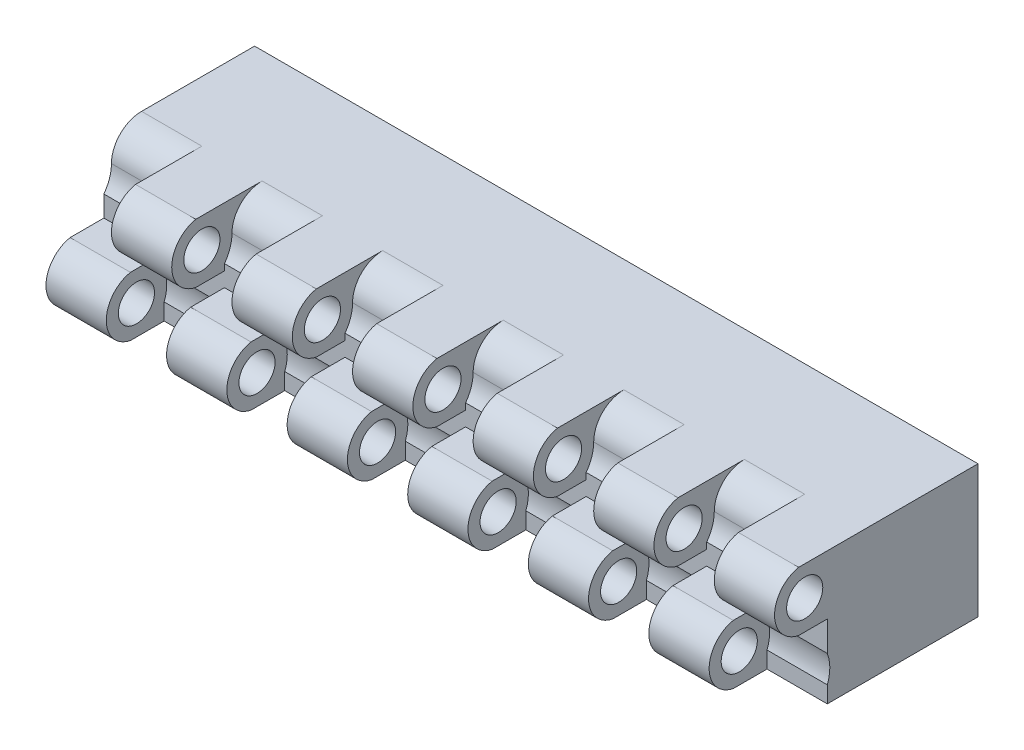
SolidWorks part; units mm, degrees
ref_plane "Front Plane" through (0, 0, 0) normal (0, 0, 1) x (1, 0, 0)
ref_plane "Top Plane" through (0, 0, 0) normal (0, 1, 0) x (1, 0, 0)
ref_plane "Right Plane" through (0, 0, 0) normal (1, 0, 0) x (0, 0, -1)
sketch "Sketch1" plane through (0, 0, 0) normal (1, 0, 0) x (0, 0, -1)
  line L1 (-12.5, 11) -> (12.5, 11)
  line L2 (-12.5, 11) -> (-12.5, -11)
  line L3 (-12.5, -11) -> (12.5, -11)
  line L4 (12.5, 11) -> (12.5, -11)
  line L5 (-12.5, 11) -> (12.5, -11) construction
  line L6 (-12.5, -11) -> (12.5, 11) construction
  point P0 (0, 0)
  dimension "D1" = 22
  dimension "D2" = 25
extrude "Boss-Extrude1" add sketch "Sketch1" along normal mid plane 120
sketch "Sketch5" plane through (60, 0, 0) normal (1, 0, 0) x (0, 0, -1)
  line L0 (-12.5, 11) -> (-12.5, 1.01) construction
  line L1 (-12.5, 11) -> (-12.5, -11) construction
  line L2 (-12.5, 6.005) -> (-17.5, 6.005) construction
  line L3 (-13.7433, 11) -> (-11.25, 11)
  line L7 (-11.25, 6.005) -> (-11.25, 11)
  arc A1 (-13.7433, 11) -> (-11.25, 6.005) centre (-17.5, 6.005) ccw
  dimension "D1" = 5
extrude "Cut-Extrude2" cut sketch "Sketch5" against normal up to next
sketch "Sketch6" plane through (-60, 0, 0) normal (-1, 0, 0) x (0, 0, 1)
  line L0 (12.5, -11) -> (12.5, -1) construction
  line L1 (12.5, 2.255) -> (12.5, -11) construction
  line L2 (12.5, -6) -> (18.3395, -6) construction
  line L3 (17.5, 6.005) -> (18.3395, -6) construction
  line L5 (12.5, -11) -> (-12.5, -11) construction
  line L6 (12.5, 11) -> (12.5, 1.01) construction
  circle A0 centre (18.3395, -6) radius 6.26
  point P9 (18.4368, -5.9847)
  point P13 (0, 0)
  dimension "D2" = 12.52
  dimension "D1" = 4
  dimension "D3" = 5
extrude "Cut-Extrude3" cut sketch "Sketch6" against normal up to next
fillet "Fillet1" radius 5 1 edges at (0, 11, 11.25)
sketch "Sketch2" plane through (60, 0, 0) normal (1, 0, 0) x (0, 0, -1)
  line L0 (-17.25, 1.202) -> (-6, 1.202)
  line L1 (-12.5, -11) -> (-12.5, 1.202) construction
  line L5 (12.5, 11) -> (-6.25, 11) construction
  line L13 (-6, 11) -> (-6, 1.202)
  line L14 (-17.25, 11) -> (-6, 11)
  arc A1 (-17.25, 11) -> (-17.25, 1.202) centre (-16.25, 6.101) ccw
  circle A2 centre (-16.25, 6.101) radius 3
  dimension "D3" = 6
  dimension "D1" = 5
  dimension "D2" = 11.25
  dimension "D4" = 5
  dimension "D5" = 9.798
extrude "Boss-Extrude2" add sketch "Sketch2" against normal blind 10
pattern_linear "LPattern1" count 6 spacing 20 along (-1, 0, 0) of "Boss-Extrude2"
sketch "Sketch3" plane through (-60, 0, 0) normal (-1, 0, 0) x (0, 0, 1)
  line L0 (12.0795, -1.202) -> (18.1033, -1.202)
  line L1 (18.1033, -11) -> (12.0795, -11)
  line L2 (12.5, -11) -> (-12.5, -11) construction
  line L8 (12.0795, -11) -> (12.0795, -1.202)
  line L9 (12.5, -11) -> (12.5, 11) construction
  line L10 (6.25, 11) -> (17.25, 11) construction
  line L11 (12.5, 6.101) -> (16.25, 6.101) construction
  line L12 (16.25, 6.101) -> (17.1033, -6.101) construction
  arc A1 (18.1033, -11) -> (18.1033, -1.202) centre (17.1033, -6.101) ccw
  circle A2 centre (17.1033, -6.101) radius 3
  arc A4 (12.5, -3.7443) -> (12.5, -8.2557) centre (18.3395, -6) ccw construction
  dimension "D3" = 6
  dimension "D4" = 9.798
  dimension "D6" = 5
  dimension "D1" = 4
extrude "Boss-Extrude3" add sketch "Sketch3" against normal blind 10
pattern_linear "LPattern2" count 6 spacing 20 along (1, 0, 0) of "Boss-Extrude3"
sketch "Sketch9" plane through (0, 0, -12.5) normal (0, 0, -1) x (-1, 0, 0)
  line L0 (-60, 11) -> (60, -11) construction
  line L1 (-12.5, 0) -> (12.5, 0) construction
  line L2 (0, 11) -> (0, -11) construction
  line L3 (-12.5, -5.5) -> (-15.5, -5.5)
  line L4 (-12.5, -5.5) -> (-12.5, 5.5)
  line L5 (-12.5, 5.5) -> (-15.5, 5.5)
  line L6 (-15.5, -5.5) -> (-15.5, 5.5)
  line L7 (-60, 11) -> (60, 11) construction
  line L8 (-60, -11) -> (60, -11) construction
  line L9 (12.5, 5.5) -> (15.5, 5.5)
  line L10 (15.5, -5.5) -> (15.5, 5.5)
  line L11 (12.5, -5.5) -> (15.5, -5.5)
  line L12 (12.5, -5.5) -> (12.5, 5.5)
  circle A0 centre (0, 0) radius 7
  point P9 (0, 0)
  point P10 (0, 0)
  dimension "D1" = 14
  dimension "D2" = 25
  dimension "D3" = 3
  dimension "D4" = 11
extrude "Cut-Extrude5" cut sketch "Sketch9" against normal blind 15
